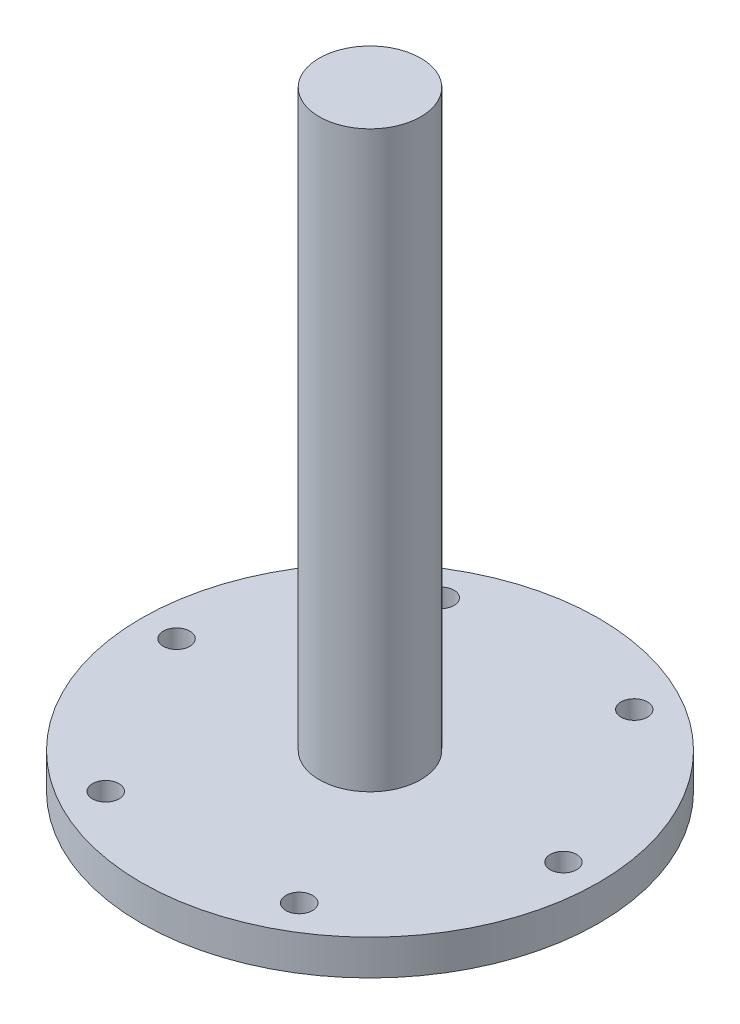
SolidWorks part; units mm, degrees
ref_plane "Спереди" through (0, 0, 0) normal (0, 0, 1) x (1, 0, 0)
ref_plane "Сверху" through (0, 0, 0) normal (0, 1, 0) x (1, 0, 0)
ref_plane "Справа" through (0, 0, 0) normal (1, 0, 0) x (0, 0, -1)
sketch "Эскиз1" plane through (0, 0, 0) normal (0, 0, 1) x (1, 0, 0)
  line L0 (0, 0) -> (0, 50000) construction
  line L1 (5.75, 0) -> (25.9, 0)
  line L2 (25.9, 0) -> (25.9, -4)
  line L3 (25.9, -4) -> (0, -4)
  line L4 (5.75, 0) -> (5.75, 65)
  line L5 (5.75, 65) -> (0, 65)
  line L6 (0, 65) -> (0, -4)
  line L7 (17.9, 60) -> (-17.9, 60) construction
  dimension "D1" = 11.5
  dimension "D2" = 4
  dimension "D3" = 5
revolve "Повернуть1" add sketch "Эскиз1" angle 360 about L0
sketch "Эскиз2" plane through (0, 0, 0) normal (0, 1, 0) x (1, 0, 0)
  circle A0 centre (21.9, 0) radius 1.5 construction
  circle A1 centre (21.9, 0) radius 1.5
  circle A2 centre (10.95, -18.966) radius 1.5
  circle A3 centre (-10.95, -18.966) radius 1.5
  circle A4 centre (-21.9, 0) radius 1.5
  circle A5 centre (-10.95, 18.966) radius 1.5
  circle A6 centre (10.95, 18.966) radius 1.5
  point P3 (7.9456, 20.2701)
  point P4 (0, 0)
  point P15 (0, 0)
  dimension "D1" = 6
extrude "Вырез-Вытянуть1" cut sketch "Эскиз2" against normal through all both and the other way through all
